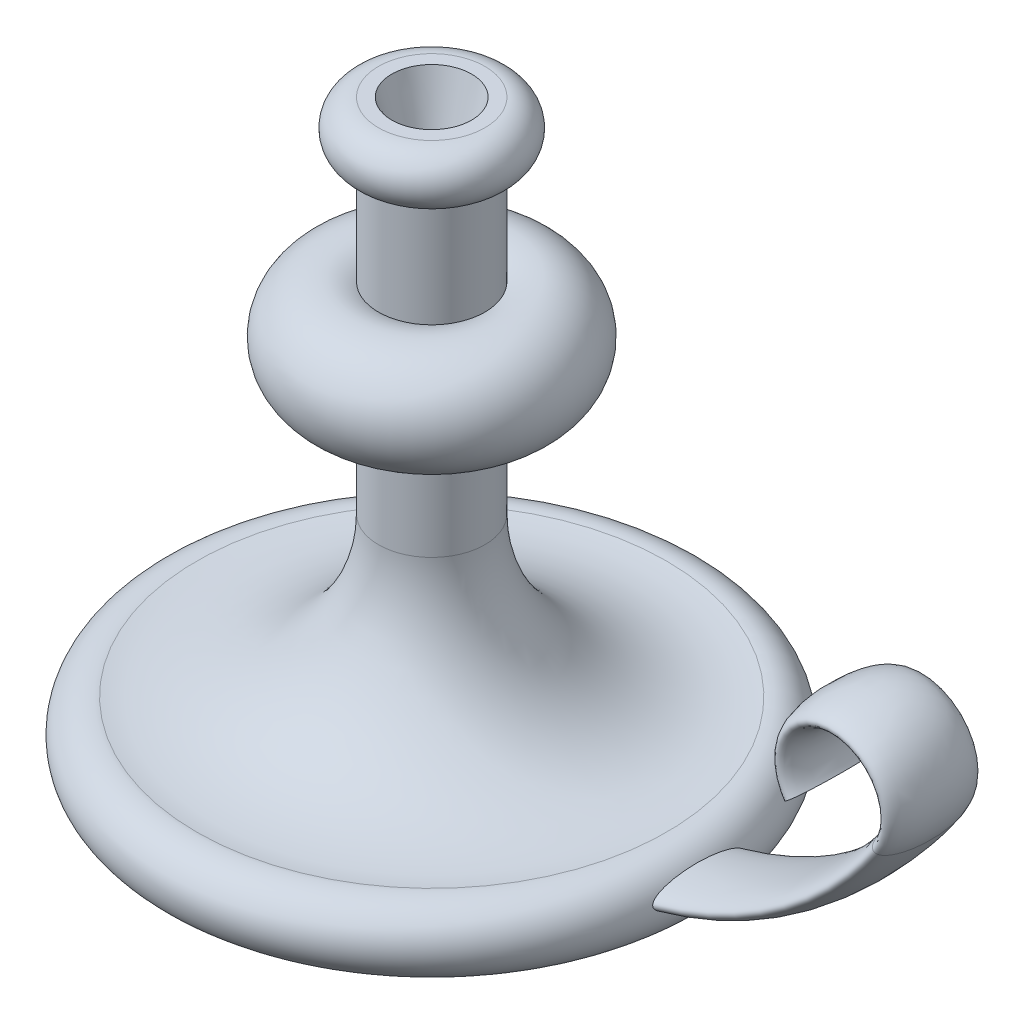
SolidWorks part; units mm, degrees
ref_plane "Front Plane" through (0, 0, 0) normal (0, 0, 1) x (1, 0, 0)
ref_plane "Top Plane" through (0, 0, 0) normal (0, 1, 0) x (1, 0, 0)
ref_plane "Right Plane" through (0, 0, 0) normal (1, 0, 0) x (0, 0, -1)
sketch "Sketch1" plane through (0, 0, 0) normal (0, 0, 1) x (1, 0, 0)
  line L0 (0, 0) -> (90, 0)
  line L1 (0, 0) -> (0, 220)
  line L2 (0, 220) -> (20, 220)
  line L3 (20, 200) -> (20, 160)
  line L4 (20, 124.307) -> (20, 84.307)
  arc A0 (20, 220) -> (20, 200) centre (20, 210) cw
  arc A1 (20, 160) -> (20, 124.307) centre (29.0279, 142.1535) cw
  arc A2 (20, 84.307) -> (88.2759, 24.8805) centre (80, 84.307) ccw
  arc A3 (88.2759, 24.8805) -> (90, 0) centre (90, 12.5) cw
  dimension "D4" = 10
  dimension "D5" = 20
  dimension "D7" = 60
  dimension "D8" = 12.5
  dimension "D1" = 20
  dimension "D2" = 220
  dimension "D3" = 90
  dimension "D6" = 40
revolve "Revolve1" add sketch "Sketch1" angle 360 about L1
sketch "Sketch2" plane through (0, 0, 0) normal (0, 0, 1) x (1, 0, 0)
  line L0 (0, 227.4356) -> (0, 175.1288) construction
  line L1 (0, 10) -> (60, 10)
  arc A0 (60, 10) -> (183.5921, 75) centre (60, 160) ccw
  arc A1 (183.5921, 75) -> (150.6342, 75) centre (167.1131, 86.3333) ccw
  dimension "D2" = 150
  dimension "D4" = 20
  dimension "D1" = 60
  dimension "D3" = 65
  dimension "D5" = 10
sketch "Sketch3" plane through (0, 0, 0) normal (1, 0, 0) x (0, 0, -1)
  ellipse E0 centre (0, 10) end of major axis (17.5, 10) minor radius 5
  dimension "D1" = 35
  dimension "D2" = 10
sweep "Sweep1" add profiles "Sketch3" path "Sketch2"
sketch "Sketch4" plane through (0, 220, 0) normal (0, 1, 0) x (1, 0, 0)
  circle A0 centre (0, 0) radius 15
  dimension "D1" = 30
extrude "Cut-Extrude1" cut sketch "Sketch4" against normal blind 25 draft 15
